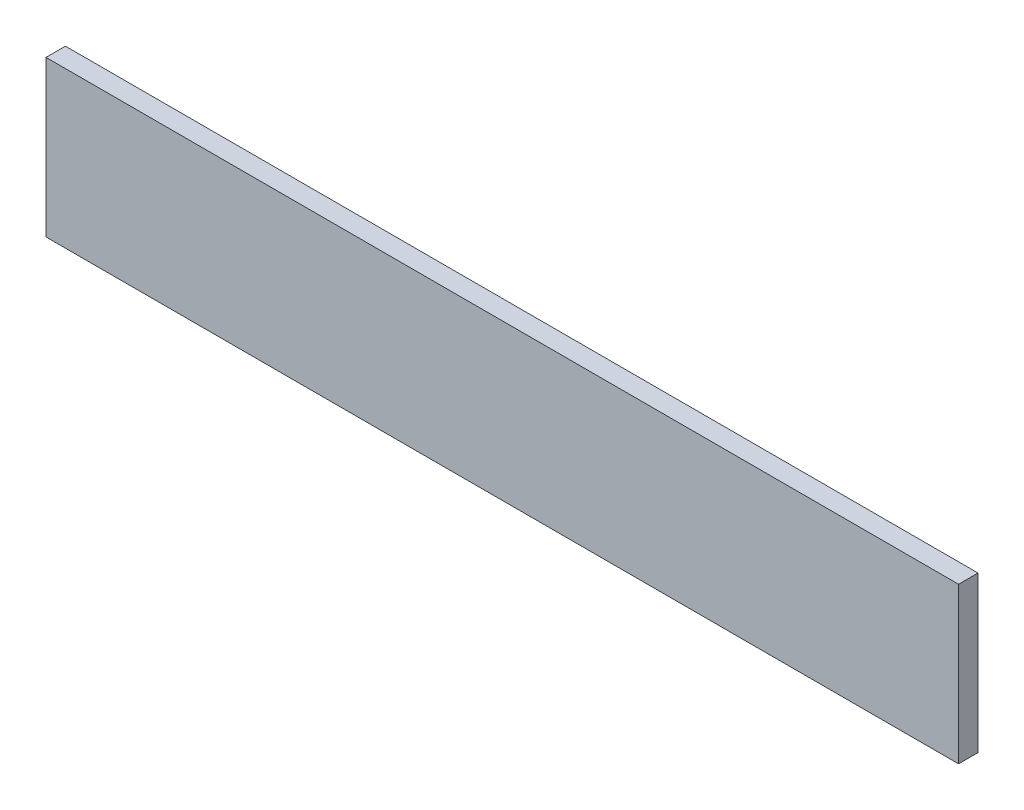
SolidWorks part; units mm, degrees
ref_plane "前视基准面" through (0, 0, 0) normal (0, 0, 1) x (1, 0, 0)
ref_plane "上视基准面" through (0, 0, 0) normal (0, 1, 0) x (1, 0, 0)
ref_plane "右视基准面" through (0, 0, 0) normal (1, 0, 0) x (0, 0, -1)
sketch "草图1" plane through (0, 0, 0) normal (0, 0, 1) x (1, 0, 0)
  line L1 (-352, 60) -> (352, 60)
  line L2 (-352, 60) -> (-352, -60)
  line L3 (-352, -60) -> (352, -60)
  line L4 (352, 60) -> (352, -60)
  line L5 (-352, 60) -> (352, -60) construction
  line L6 (-352, -60) -> (352, 60) construction
  point P0 (0, 0)
  dimension "D1" = 120
  dimension "D2" = 704
extrude "凸台-拉伸1" add sketch "草图1" along normal blind 15
